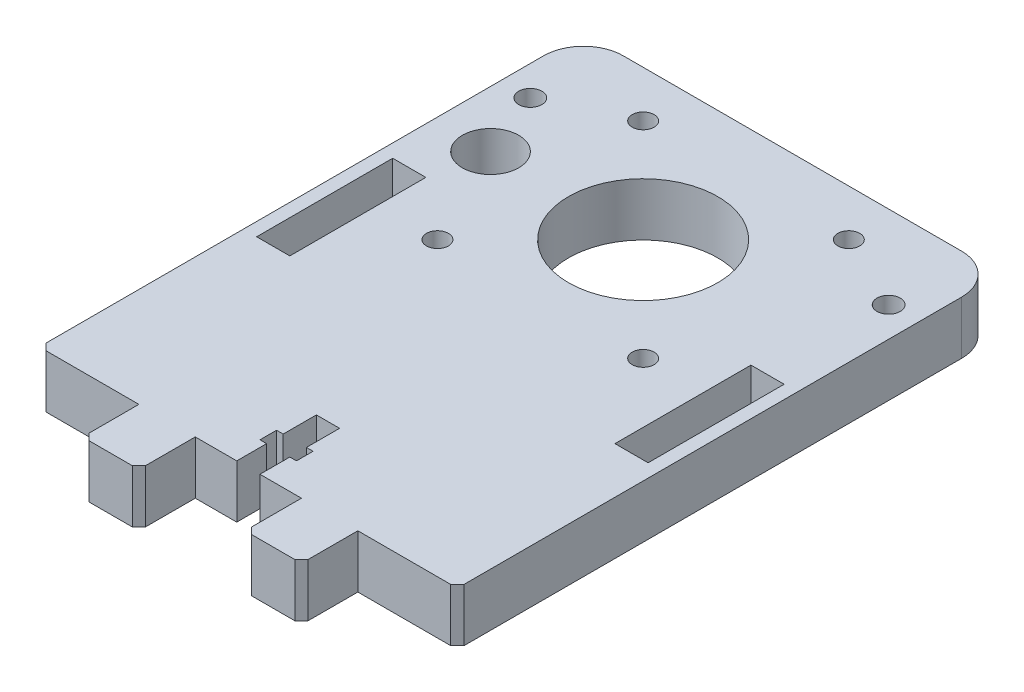
SolidWorks part; units mm, degrees
ref_plane "Front Plane" through (0, 0, 0) normal (0, 0, 1) x (1, 0, 0)
ref_plane "Top Plane" through (0, 0, 0) normal (0, 1, 0) x (1, 0, 0)
ref_plane "Right Plane" through (0, 0, 0) normal (1, 0, 0) x (0, 0, -1)
sketch "Sketch1" plane through (0, 0, 0) normal (0, 1, 0) x (1, 0, 0)
  line L0 (4.8942, 14.4947) -> (4.8942, 89.4947)
  line L1 (10.8942, 95.4947) -> (61.8942, 95.4947)
  line L2 (67.8942, 89.4947) -> (67.8942, 14.4947)
  line L3 (67.8942, 14.4947) -> (66.8942, 13.4947)
  line L4 (66.8942, 13.4947) -> (52.8942, 13.4947)
  line L5 (52.8942, 13.4947) -> (52.8942, 5.9947)
  line L6 (52.8942, 5.9947) -> (51.8942, 4.9947)
  line L7 (51.8942, 4.9947) -> (45.3942, 4.9947)
  line L8 (45.3942, 4.9947) -> (44.3942, 5.9947)
  line L9 (44.3942, 5.9947) -> (44.3942, 13.4947)
  line L10 (44.3942, 13.4947) -> (38.1442, 13.4947)
  line L11 (38.1442, 13.4947) -> (38.1442, 17.9947)
  line L12 (38.1442, 17.9947) -> (39.1442, 17.9947)
  line L13 (39.1442, 17.9947) -> (39.1442, 20.4947)
  line L14 (39.1442, 20.4947) -> (38.1442, 20.4947)
  line L15 (38.1442, 20.4947) -> (38.1442, 25.4947)
  line L16 (38.1442, 25.4947) -> (34.6442, 25.4947)
  line L17 (34.6442, 25.4947) -> (34.6442, 20.4947)
  line L18 (34.6442, 20.4947) -> (33.6442, 20.4947)
  line L19 (33.6442, 20.4947) -> (33.6442, 17.9947)
  line L20 (33.6442, 17.9947) -> (34.6442, 17.9947)
  line L21 (34.6442, 17.9947) -> (34.6442, 13.4947)
  line L22 (34.6442, 13.4947) -> (28.3942, 13.4947)
  line L23 (28.3942, 13.4947) -> (28.3942, 5.9947)
  line L24 (28.3942, 5.9947) -> (27.3942, 4.9947)
  line L25 (27.3942, 4.9947) -> (20.8942, 4.9947)
  line L26 (20.8942, 4.9947) -> (19.8942, 5.9947)
  line L27 (19.8942, 5.9947) -> (19.8942, 13.4947)
  line L28 (19.8942, 13.4947) -> (5.8942, 13.4947)
  line L29 (5.8942, 13.4947) -> (4.8942, 14.4947)
  line L30 (6.8942, 64.7447) -> (11.8942, 64.7447)
  line L31 (11.8942, 64.7447) -> (11.8942, 44.2447)
  line L32 (11.8942, 44.2447) -> (6.8942, 44.2447)
  line L33 (6.8942, 44.2447) -> (6.8942, 64.7447)
  line L34 (65.8942, 64.7447) -> (60.8942, 64.7447)
  line L35 (60.8942, 64.7447) -> (60.8942, 44.2447)
  line L36 (60.8942, 44.2447) -> (65.8942, 44.2447)
  line L37 (65.8942, 44.2447) -> (65.8942, 64.7447)
  arc A0 (10.8942, 95.4947) -> (4.8942, 89.4947) centre (10.8942, 89.4947) ccw
  arc A1 (67.8942, 89.4947) -> (61.8942, 95.4947) centre (61.8942, 89.4947) ccw
  circle A2 centre (13.3942, 72.9947) radius 4.25
  circle A3 centre (51.8942, 88.4947) radius 1.65
  circle A4 centre (20.8942, 88.4947) radius 1.65
  circle A5 centre (51.8942, 57.4947) radius 1.65
  circle A6 centre (20.8942, 57.4947) radius 1.65
  circle A9 centre (36.3942, 72.9947) radius 11.25
extrude "Extrude1" add sketch "Sketch1" along normal blind 8
sketch "Sketch2" plane through (0, 0, -25.4947) normal (0, 0, 1) x (1, 0, 0)
  line L0 (34.6442, 8) -> (38.1442, 0)
  circle A0 centre (36.3942, 4) radius 1
  dimension "D1" = 2
extrude "Extrude2" cut sketch "Sketch2" against normal blind 1 contours A0
sketch "Sketch3" plane through (0, 8, 0) normal (0, 1, 0) x (1, 0, 0)
  line L0 (36.3942, 95.4947) -> (36.3942, 82.9947) construction
  line L1 (61.8942, 95.4947) -> (10.8942, 95.4947) construction
  line L2 (63.3942, 82.9947) -> (9.3942, 82.9947) construction
  circle A0 centre (9.3942, 82.9947) radius 1.75
  circle A1 centre (63.3942, 82.9947) radius 1.75
  dimension "D4" = 3.5
  dimension "D5" = 3.5
  dimension "D1" = 12.5
  dimension "D2" = 27
  dimension "D3" = 54
extrude "Extrude3" cut sketch "Sketch3" against normal blind 10
